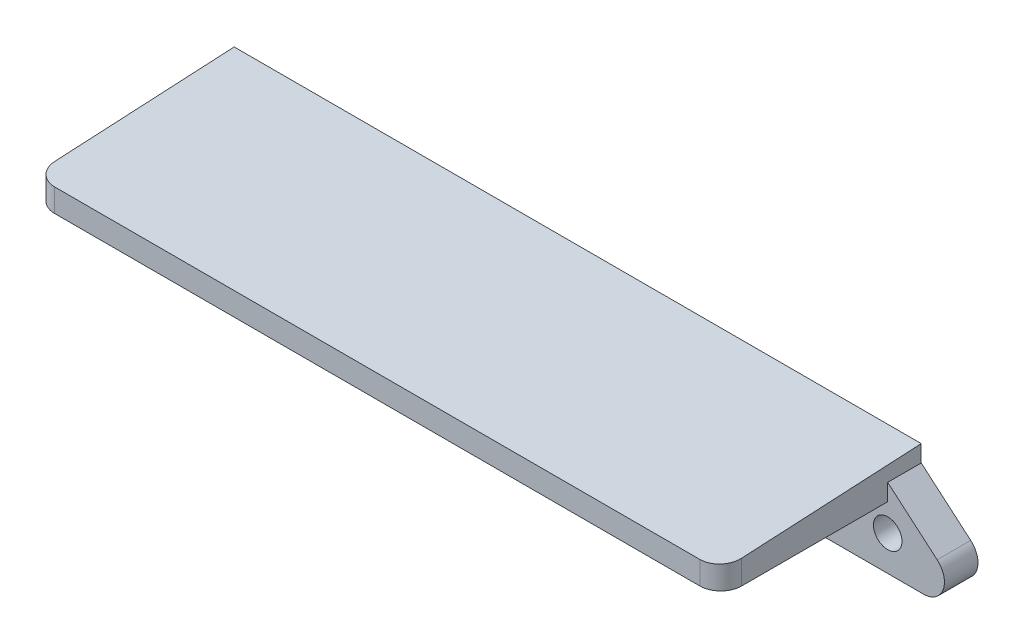
SolidWorks part; units mm, degrees
material "Commercial Bronze, UNS C22000 (90-10 Bronze)"
ref_plane "Top Plane" through (0, 0, 0) normal (0, 0, 1) x (1, 0, 0)
ref_plane "Front Plane" through (0, 0, 0) normal (0, 1, 0) x (1, 0, 0)
ref_plane "Right Plane" through (0, 0, 0) normal (1, 0, 0) x (0, 0, -1)
sketch "Sketch1" plane through (0, 0, 0) normal (0, 0, 1) x (1, 0, 0)
  line L0 (-51.95, 0) -> (51.95, 0)
  line L1 (51.95, 0) -> (40.95, 9.4088)
  line L2 (40.95, 9.4088) -> (-40.95, 9.4088)
  line L3 (0, 0) -> (0, 55.8461) construction
  line L4 (-51.95, 0) -> (-40.95, 9.4088)
  point P9 (0, 9.4088)
  dimension "D1" = 51.95
  dimension "D2" = 40.95
  dimension "D3" = 14.475
extrude "Boss-Extrude1" add sketch "Sketch1" along normal blind 4
fillet "Fillet1" radius 2.48 2 edges at (51.95, 0, 2) (-51.95, 0, 2)
sketch "Sketch4" plane through (0, 9.4088, 0) normal (0, 1, 0) x (1, 0, 0)
  line L4 (40.95, 0) -> (-40.95, 0)
  line L5 (-40.95, 0) -> (-40.95, -4)
  line L6 (-40.95, -4) -> (40.95, -4)
  line L7 (40.95, -4) -> (40.95, 0)
  line L8 (40.95, 0) -> (-40.95, 0)
  line L9 (-40.95, 0) -> (-40.95, -4)
  line L10 (-40.95, -4) -> (40.95, -4)
  line L11 (40.95, -4) -> (40.95, 0)
  dimension "D1" = 0
extrude "Boss-Extrude3" add sketch "Sketch4" along normal blind 2
sketch "Sketch6" plane through (0, 0, 4) normal (0, 0, 1) x (1, 0, 0)
  line L1 (-40.95, 11.4088) -> (40.95, 11.4088)
  line L2 (-40.95, 11.4088) -> (-40.95, 7.4088)
  line L3 (-40.95, 7.4088) -> (40.95, 7.4088)
  line L4 (40.95, 11.4088) -> (40.95, 7.4088)
  dimension "D1" = 4
extrude "Boss-Extrude4" add sketch "Sketch6" along normal blind 19.9
fillet "Fillet3" radius 2.5 2 edges at (40.95, 9.4088, 23.9) (-40.95, 9.4088, 23.9)
sketch "Sketch7" plane through (0, 11.4088, 0) normal (0, 1, 0) x (1, 0, 0)
  line L1 (-40.95, 0) -> (40.95, 0)
  line L2 (-40.95, 0) -> (-40.95, -35.8017)
  line L3 (-40.95, -35.8017) -> (40.95, -35.8017)
  line L4 (40.95, 0) -> (40.95, -35.8017)
revolve "Cut-Revolve2" cut sketch "Sketch7" angle 3 about L1
sketch "Sketch8" plane through (0, 0, 0) normal (0, 0, -1) x (-1, 0, 0)
  line L0 (-40.95, 9.4088) -> (-40.95, 0) construction
  line L1 (45.2352, 0) -> (-45.2352, 0) construction
  line L3 (40.95, 9.4088) -> (40.95, 0) construction
  point P0 (-40.95, 4.1588)
  point P3 (40.95, 4.1588)
  dimension "D1" = 5.25
  dimension "D2" = 5.25
hole_wizard "CSK for M3 Flat Head Machine Screw1" positions "Sketch8" profile "Sketch9" countersink size "M3" standard "ANSI Metric"
sketch "Sketch9" plane through (40.95, 4.1588, 0) normal (1, 0, 0) x (0, 1, 0)
  line L0 (0, 0) -> (0, 11.1215)
  line L1 (0, 11.1215) -> (1.7, 10.1)
  line L2 (1.7, 10.1) -> (1.7, 1.45)
  line L3 (1.7, 1.45) -> (3.15, 0)
  line L5 (3.15, 0) -> (0, 0)
  line L6 (-1.7, 1.45) -> (-3.15, 0) construction
  line L10 (0, 11.1215) -> (-1.7, 10.1) construction
  line L11 (0, -6.35) -> (0, 107.95) construction
  dimension "Hole Dia." = 3.4
  dimension "Hole Depth" = 10.1
  dimension "Near C'Sink Dia." = 6.3
  dimension "Near C'Sink Angle" = 90
  dimension "Drill Angle" = 118
